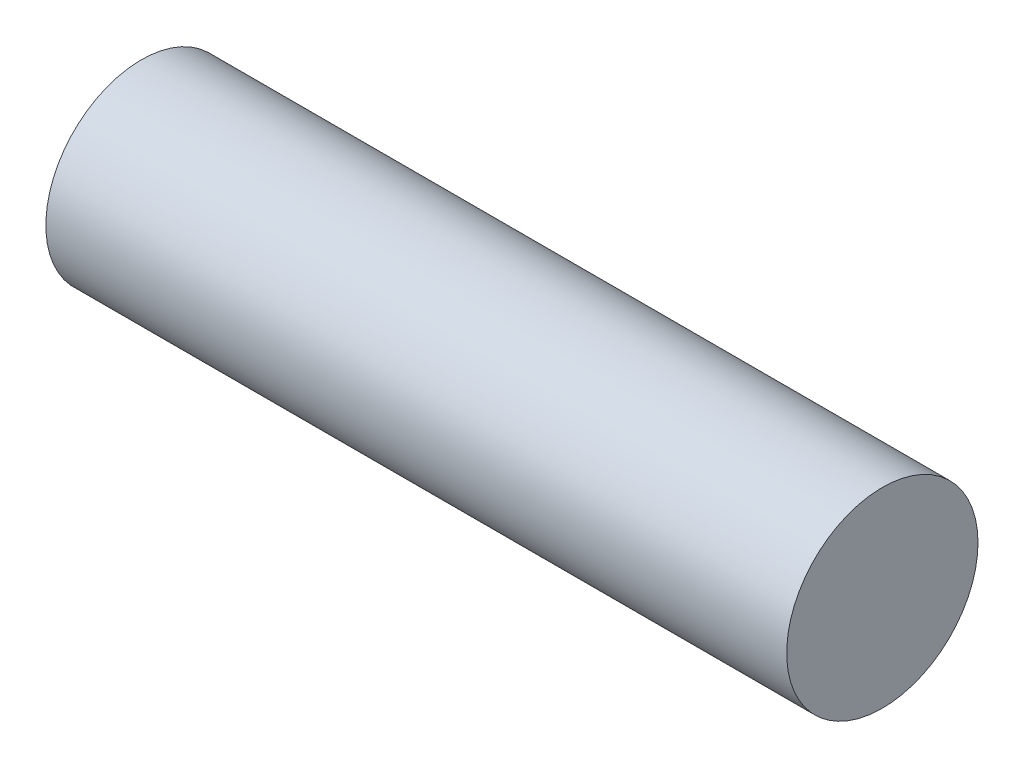
SolidWorks part; units mm, degrees
ref_plane "Front Plane" through (0, 0, 0) normal (0, 0, 1) x (1, 0, 0)
ref_plane "Top Plane" through (0, 0, 0) normal (0, 1, 0) x (1, 0, 0)
ref_plane "Right Plane" through (0, 0, 0) normal (1, 0, 0) x (0, 0, -1)
sketch "Sketch3" plane through (0, 0, 0) normal (1, 0, 0) x (0, 0, -1)
  line L0 (-65.6269, 0) -> (65.6269, 0) construction
  line L1 (0, 65.6269) -> (0, -65.6269) construction
  circle A1 centre (0, 0) radius 65.6269
  point P8 (0, 0)
extrude "Boss-Extrude2" add sketch "Sketch3" along normal blind 508.254
